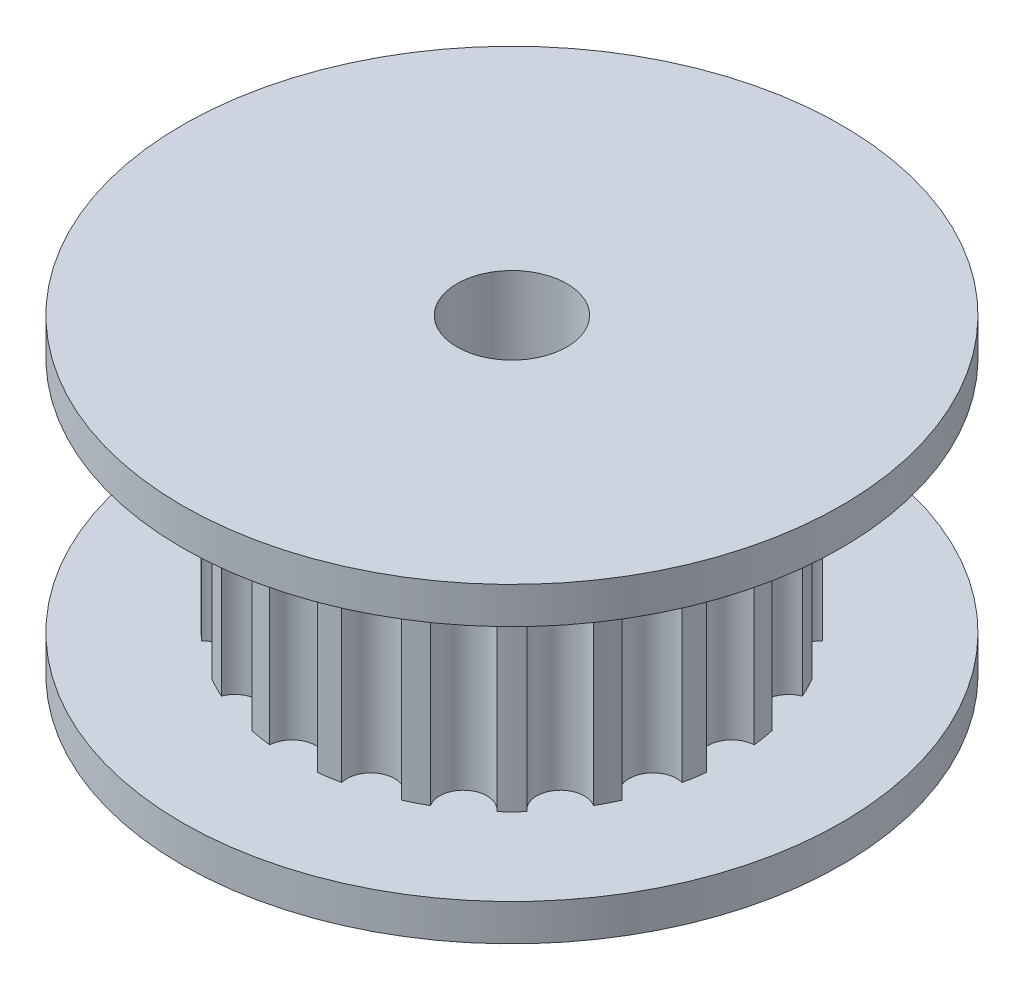
SolidWorks part; units mm, degrees
ref_plane "前视基准面" through (0, 0, 0) normal (0, 0, 1) x (1, 0, 0)
ref_plane "上视基准面" through (0, 0, 0) normal (0, 1, 0) x (1, 0, 0)
ref_plane "右视基准面" through (0, 0, 0) normal (1, 0, 0) x (0, 0, -1)
sketch "草图1" plane through (0, 0, 0) normal (0, 1, 0) x (1, 0, 0)
  circle A0 centre (0, 0) radius 9
  dimension "D1" = 18
extrude "凸台-拉伸1" add sketch "草图1" along normal blind 1
sketch "草图2" plane through (0, 1, 0) normal (0, 1, 0) x (1, 0, 0)
  circle A0 centre (0, 0) radius 6
  dimension "D1" = 12
extrude "凸台-拉伸2" add sketch "草图2" along normal blind 6.5
sketch "草图3" plane through (0, 7.5, 0) normal (0, 1, 0) x (1, 0, 0)
  circle A0 centre (0, 6) radius 0.65
  circle A1 centre (0, 0) radius 6 construction
  circle A2 centre (1.8541, 5.7063) radius 0.65
  circle A3 centre (3.5267, 4.8541) radius 0.65
  circle A4 centre (4.8541, 3.5267) radius 0.65
  circle A5 centre (5.7063, 1.8541) radius 0.65
  circle A6 centre (6, 0) radius 0.65
  circle A7 centre (5.7063, -1.8541) radius 0.65
  circle A8 centre (4.8541, -3.5267) radius 0.65
  circle A9 centre (3.5267, -4.8541) radius 0.65
  circle A10 centre (1.8541, -5.7063) radius 0.65
  circle A11 centre (0, -6) radius 0.65
  circle A12 centre (-1.8541, -5.7063) radius 0.65
  circle A13 centre (-3.5267, -4.8541) radius 0.65
  circle A14 centre (-4.8541, -3.5267) radius 0.65
  circle A15 centre (-5.7063, -1.8541) radius 0.65
  circle A16 centre (-6, 0) radius 0.65
  circle A17 centre (-5.7063, 1.8541) radius 0.65
  circle A18 centre (-4.8541, 3.5267) radius 0.65
  circle A19 centre (-3.5267, 4.8541) radius 0.65
  circle A20 centre (-1.8541, 5.7063) radius 0.65
  point P45 (0, 0)
  dimension "D1" = 1.3
  dimension "D2" = 20
extrude "切除-拉伸1" cut sketch "草图3" against normal blind 6.5
sketch "草图5" plane through (0, 7.5, 0) normal (0, 1, 0) x (1, 0, 0)
  circle A0 centre (0, 0) radius 9
  dimension "D1" = 18
extrude "凸台-拉伸3" add sketch "草图5" along normal blind 1
sketch "草图6" plane through (0, 8.5, 0) normal (0, 1, 0) x (1, 0, 0)
  circle A0 centre (0, 0) radius 1.5
  dimension "D1" = 3
extrude "切除-拉伸2" cut sketch "草图6" against normal through all
